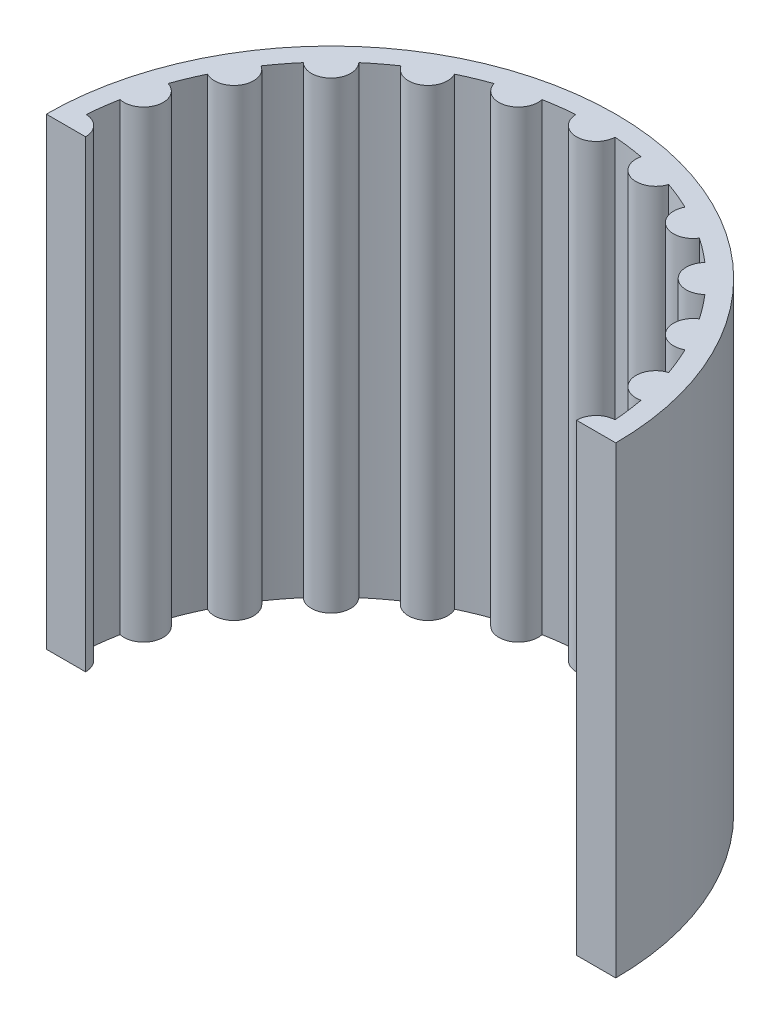
SolidWorks part; units mm, degrees
material "Polyurethane Foam Flexible"
ref_plane "Front" through (0, 0, 0) normal (0, 0, 1) x (1, 0, 0)
ref_plane "Top" through (0, 0, 0) normal (0, 1, 0) x (1, 0, 0)
ref_plane "Right" through (0, 0, 0) normal (1, 0, 0) x (0, 0, -1)
sketch "Sketch1" plane through (0, 0, 0) normal (0, 1, 0) x (1, 0, 0)
  line L3 (158.75, 0) -> (184.15, 0)
  line L4 (-184.15, 0) -> (-158.75, 0)
  arc A0 (184.15, 0) -> (-184.15, 0) centre (0, 0) ccw
  arc A1 (170.9796, 12.6913) -> (168.4384, 31.9939) centre (0, 0) ccw
  arc A3 (-158.75, 0) -> (-170.9796, 12.6913) centre (-171.45, 0) ccw
  arc A4 (-168.4384, 31.9939) -> (-161.8689, 56.5116) centre (-165.608, 44.3745) ccw
  arc A5 (-154.4183, 74.4988) -> (-141.7271, 96.4808) centre (-148.4801, 85.725) ccw
  arc A6 (-129.875, 111.9268) -> (-111.9268, 129.875) centre (-121.2335, 121.2335) ccw
  arc A7 (-96.4808, 141.7271) -> (-74.4988, 154.4183) centre (-85.725, 148.4801) ccw
  arc A8 (-56.5116, 161.8689) -> (-31.9939, 168.4384) centre (-44.3745, 165.608) ccw
  arc A9 (-12.6913, 170.9796) -> (12.6913, 170.9796) centre (0, 171.45) ccw
  arc A10 (31.9939, 168.4384) -> (56.5116, 161.8689) centre (44.3745, 165.608) ccw
  arc A11 (74.4988, 154.4183) -> (96.4808, 141.7271) centre (85.725, 148.4801) ccw
  arc A12 (111.9268, 129.875) -> (129.875, 111.9268) centre (121.2335, 121.2335) ccw
  arc A13 (141.7271, 96.4808) -> (154.4183, 74.4988) centre (148.4801, 85.725) ccw
  arc A14 (161.8689, 56.5116) -> (168.4384, 31.9939) centre (165.608, 44.3745) ccw
  arc A15 (170.9796, 12.6913) -> (158.75, 0) centre (171.45, 0) ccw
  arc A16 (161.8689, 56.5116) -> (154.4183, 74.4988) centre (0, 0) ccw
  arc A17 (141.7271, 96.4808) -> (129.875, 111.9268) centre (0, 0) ccw
  arc A18 (111.9268, 129.875) -> (96.4808, 141.7271) centre (0, 0) ccw
  arc A19 (74.4988, 154.4183) -> (56.5116, 161.8689) centre (0, 0) ccw
  arc A20 (31.9939, 168.4384) -> (12.6913, 170.9796) centre (0, 0) ccw
  arc A21 (-12.6913, 170.9796) -> (-31.9939, 168.4384) centre (0, 0) ccw
  arc A22 (-56.5116, 161.8689) -> (-74.4988, 154.4183) centre (0, 0) ccw
  arc A23 (-96.4808, 141.7271) -> (-111.9268, 129.875) centre (0, 0) ccw
  arc A24 (-129.875, 111.9268) -> (-141.7271, 96.4808) centre (0, 0) ccw
  arc A25 (-154.4183, 74.4988) -> (-161.8689, 56.5116) centre (0, 0) ccw
  arc A26 (-168.4384, 31.9939) -> (-170.9796, 12.6913) centre (0, 0) ccw
  point P34 (0, 0)
  dimension "D1" = 13
  dimension "D2" = 184.15
  dimension "D3" = 171.45
  dimension "D4" = 12.7
extrude "Boss-Extrude1" add sketch "Sketch1" against normal blind 299.72
